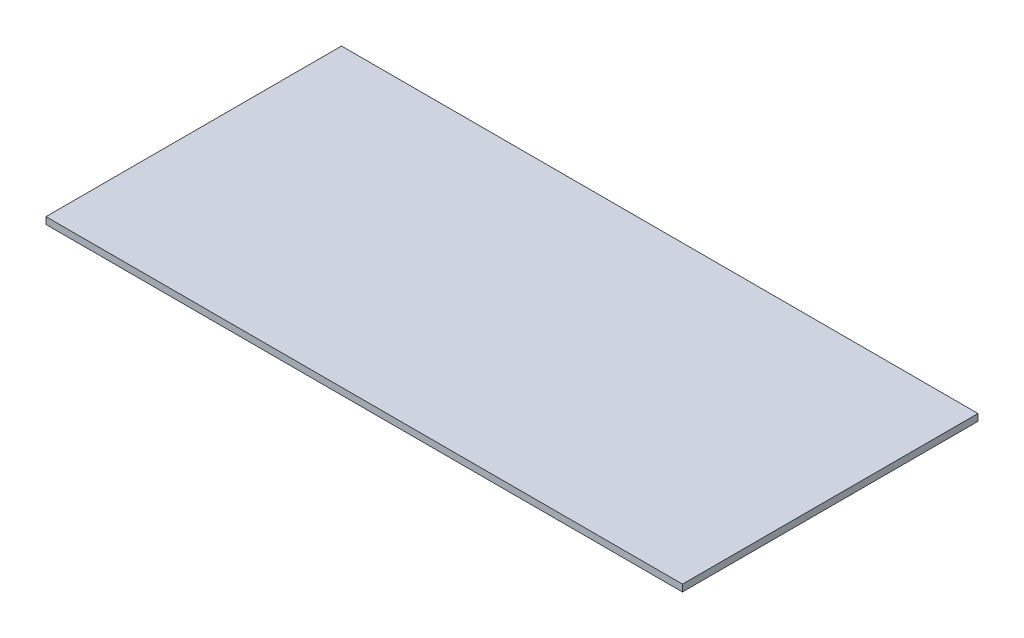
SolidWorks part; units mm, degrees
ref_plane "Front Plane" through (0, 0, 0) normal (0, 0, 1) x (1, 0, 0)
ref_plane "Top Plane" through (0, 0, 0) normal (0, 1, 0) x (1, 0, 0)
ref_plane "Right Plane" through (0, 0, 0) normal (1, 0, 0) x (0, 0, -1)
sketch "Sketch1" plane through (0, 0, 0) normal (0, 1, 0) x (1, 0, 0)
  line L1 (0, 45.589) -> (-280, 45.589)
  line L2 (0, 45.589) -> (0, -84.411)
  line L3 (0, -84.411) -> (-280, -84.411)
  line L4 (-280, 45.589) -> (-280, -84.411)
  dimension "D1" = 280
  dimension "D2" = 130
extrude "Boss-Extrude1" add sketch "Sketch1" along normal blind 3
